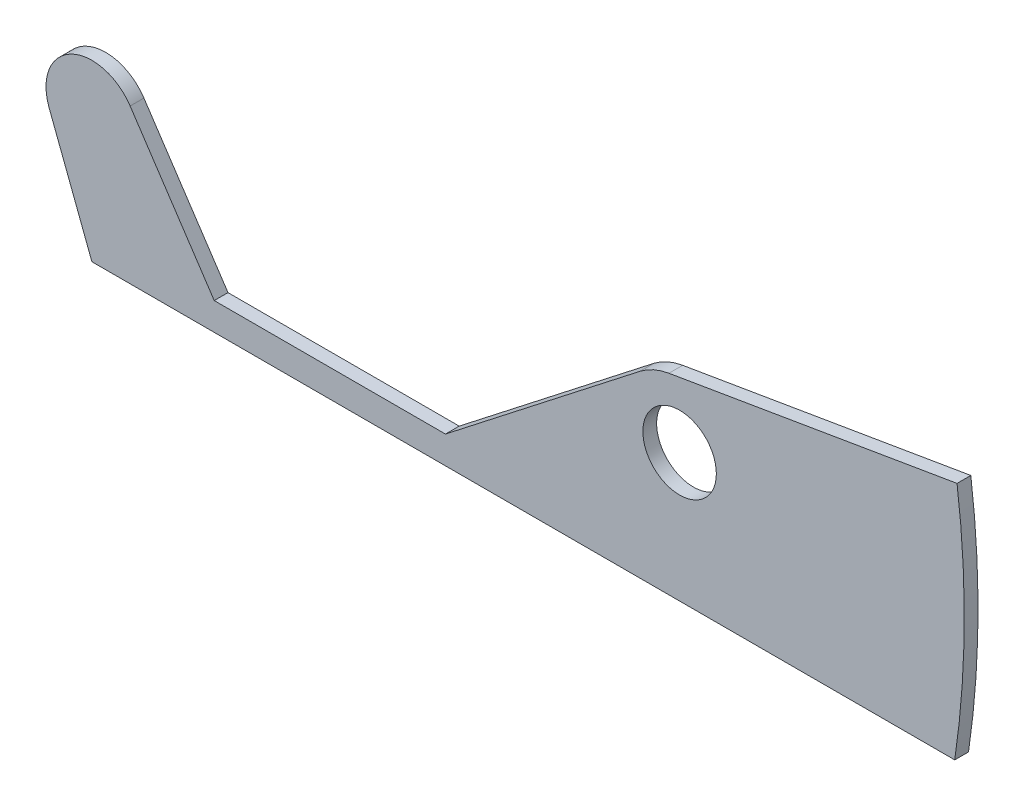
SolidWorks part; units mm, degrees
ref_plane "Спереди" through (0, 0, 0) normal (0, 0, 1) x (1, 0, 0)
ref_plane "Сверху" through (0, 0, 0) normal (0, 1, 0) x (1, 0, 0)
ref_plane "Справа" through (0, 0, 0) normal (1, 0, 0) x (0, 0, -1)
sketch "Эскиз1" plane through (0, 0, 0) normal (0, 0, 1) x (1, 0, 0)
  line L0 (-31.9542, -25) -> (253.1565, -25) construction
  line L1 (9, 35.6094) -> (9, -47.5785) construction
  line L2 (-39.2405, -28) -> (262.4545, -28) construction
  line L3 (-31.9542, -22) -> (262.4545, -22) construction
  line L4 (-9.3405, -3.5714) -> (0, -28)
  line L5 (8.3266, 5.5379) -> (26.6416, -22)
  line L6 (-26.4187, 0) -> (187.6558, 0) construction
  line L7 (119.3936, 11.0422) -> (77, -22)
  line L8 (77, -22) -> (26.6416, -22)
  line L9 (0, 0) -> (183.9369, 4.8166) construction
  line L10 (0, 0) -> (183.9369, -4.8166) construction
  line L11 (0, 0) -> (183.4328, -14.4365) construction
  line L12 (0, 0) -> (183.4328, 14.4365) construction
  line L13 (125.6674, 13.8043) -> (188.4256, 24.4092)
  line L14 (0, -28) -> (187.9255, -28)
  line L15 (43, -17.0585) -> (43, -35.954) construction
  line L16 (77, -17.0585) -> (77, -35.954) construction
  arc A0 (8.3266, 5.5379) -> (-9.3405, -3.5714) centre (0, 0) ccw
  circle A1 centre (128, 0) radius 8
  arc A2 (125.6674, 13.8043) -> (119.3936, 11.0422) centre (128, 0) ccw
  circle A3 centre (0, 0) radius 184 construction
  arc A4 (187.9255, -28) -> (188.4256, 24.4092) centre (0, 0) ccw
  dimension "D1" = 20
  dimension "D2" = 25
  dimension "D3" = 9
  dimension "D6" = 16
  dimension "D8" = 28
  dimension "D9" = 368
  dimension "D10" = 34
  dimension "D4" = 6
  dimension "D5" = 3
  dimension "D7" = 128
  dimension "D11" = 3
  dimension "D12" = 3
  dimension "D13" = 3
  dimension "D14" = 1.5
  dimension "D15" = 34
extrude "Бобышка-Вытянуть1" add sketch "Эскиз1" along normal blind 3
equation "\"D12@Эскиз1\"=\"D11@Эскиз1\""
equation "\"D13@Эскиз1\"=\"D11@Эскиз1\""
equation "\"D14@Эскиз1\"=\"D11@Эскиз1\"/2"
